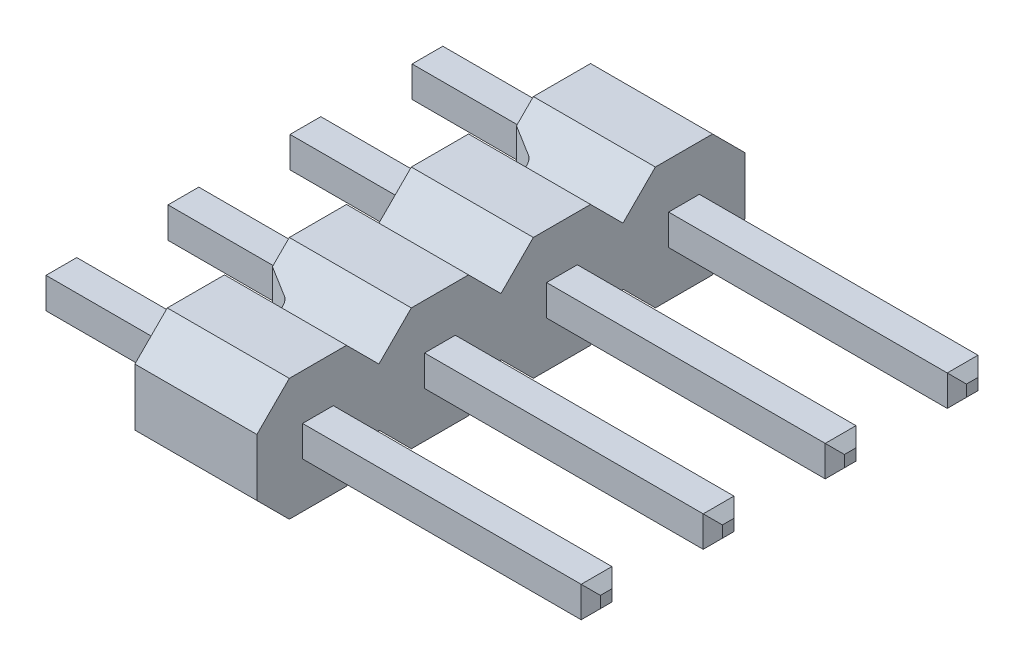
SolidWorks part; units mm, degrees
ref_plane "Alzado" through (0, 0, 0) normal (0, 0, 1) x (1, 0, 0)
ref_plane "Planta" through (0, 0, 0) normal (0, 1, 0) x (1, 0, 0)
ref_plane "Vista lateral" through (0, 0, 0) normal (1, 0, 0) x (0, 0, -1)
sketch "Croquis1" plane through (0, 0, 0) normal (1, 0, 0) x (0, 0, -1)
  line L0 (-0.5955, 1.27) -> (-1.27, 0.5955)
  line L1 (0.5955, 1.27) -> (-0.5955, 1.27)
  line L2 (1.27, 0.5955) -> (1.27, -0.5955)
  line L3 (0.5955, -1.27) -> (-0.5955, -1.27)
  line L4 (-1.27, 0.5955) -> (-1.27, -0.5955)
  line L5 (1.27, 1.27) -> (-1.27, -1.27) construction
  line L6 (1.27, -1.27) -> (-1.27, 1.27) construction
  line L7 (-0.5955, -1.27) -> (-1.27, -0.5955)
  line L8 (1.27, -0.5955) -> (0.5955, -1.27)
  line L9 (1.27, 0.5955) -> (0.5955, 1.27)
  line L10 (0, 0) -> (2.54, 0) construction
  line L11 (2.54, 0) -> (2.54, 3.1915) construction
  line L12 (0, 0) -> (0, 2.4434) construction
  line L13 (1.27, 0.5955) -> (1.27, 2.4434) construction
  line L14 (1.27, -0.5955) -> (1.9445, -1.27)
  line L15 (1.27, 0.5955) -> (1.9445, 1.27)
  line L16 (3.1355, -1.27) -> (3.81, -0.5955)
  line L17 (3.81, 0.5955) -> (3.81, -0.5955)
  line L18 (1.9445, -1.27) -> (3.1355, -1.27)
  line L19 (1.9445, 1.27) -> (3.1355, 1.27)
  line L20 (3.1355, 1.27) -> (3.81, 0.5955)
  line L21 (2.22, -0.32) -> (2.86, 0.32) construction
  line L22 (0.32, 0.32) -> (-0.32, 0.32)
  line L23 (0.32, 0.32) -> (0.32, -0.32)
  line L24 (0.32, -0.32) -> (-0.32, -0.32)
  line L25 (-0.32, 0.32) -> (-0.32, -0.32)
  line L26 (0.32, 0.32) -> (-0.32, -0.32) construction
  line L27 (0.32, -0.32) -> (-0.32, 0.32) construction
  line L28 (2.22, 0.32) -> (2.86, -0.32) construction
  line L29 (2.86, 0.32) -> (2.86, -0.32)
  line L30 (2.22, -0.32) -> (2.86, -0.32)
  line L31 (2.22, 0.32) -> (2.22, -0.32)
  line L32 (2.22, 0.32) -> (2.86, 0.32)
  point P0 (0, 0)
  dimension "D1" = 2.54
  dimension "D2" = 2.54
  dimension "D3" = 2.54
  dimension "D4" = 0.64
  dimension "D5" = 0.64
extrude "Saliente-Extruir1" add sketch "Croquis1" along normal blind 2.54 contours L2 L9 L1 L0 L4 L7 L3 L8 L25 L22 L23 L24 | L20 L19 L15 L2 L14 L18 L16 L17 L31 L32 L29 L30
sketch "Croquis2" plane through (0, 0, 0) normal (0, 1, 0) x (1, 0, 0)
  line L0 (0, 1.27) -> (0.5165, 1.27) construction
  line L1 (2.54, 1.27) -> (0, 1.27) construction
  line L2 (0.5165, 1.2433) -> (0.5165, 1.2967)
  line L3 (0.4575, 1.3879) -> (0, 1.5936)
  line L4 (0, 1.27) -> (0, 1.9445) construction
  line L5 (0.4575, 1.1521) -> (0, 0.9464)
  line L6 (0, 1.5936) -> (0, 0.9464)
  arc A0 (0.5165, 1.2967) -> (0.4575, 1.3879) centre (0.4165, 1.2967) ccw
  arc A1 (0.5165, 1.2433) -> (0.4575, 1.1521) centre (0.4165, 1.2433) cw
  dimension "D1" = 0.1
extrude "Cortar-Extruir1" cut sketch "Croquis2" against normal blind 2.54 and the other way blind 2.54
sketch "Croquis3" plane through (0, 0, 0) normal (1, 0, 0) x (0, 0, -1)
  line L1 (-0.32, -0.32) -> (0.32, -0.32)
  line L2 (-0.32, -0.32) -> (-0.32, 0.32)
  line L3 (-0.32, 0.32) -> (0.32, 0.32)
  line L4 (0.32, -0.32) -> (0.32, 0.32)
  line L5 (2.22, -0.32) -> (2.86, -0.32)
  line L6 (2.22, -0.32) -> (2.22, 0.32)
  line L7 (2.22, 0.32) -> (2.86, 0.32)
  line L8 (2.86, -0.32) -> (2.86, 0.32)
extrude "Saliente-Extruir2" add sketch "Croquis3" along normal blind 8.54 and the other way blind 3 separate body
chamfer "Chaflán1" distance 0.2 angle 45 8 edges at (-3, -0.32, 0) (-3, 0, -0.32) (-3, 0.32, 0) (-3, 0, 0.32) (8.54, 0.32, 0) (8.54, 0, -0.32) (8.54, -0.32, 0) (8.54, 0, 0.32)
chamfer "Chaflán2" distance 0.2 angle 45 8 edges at (8.54, 0.32, -2.54) (8.54, 0, -2.86) (8.54, -0.32, -2.54) (8.54, 0, -2.22) (-3, -0.32, -2.54) (-3, 0, -2.86) (-3, 0.32, -2.54) (-3, 0, -2.22)
mirror "Mirror3" about plane through (2.54, 0, 1.27) normal (0, 0, -1) of bodies 104 103
mirror "Mirror5" about plane through (2.54, 0, 1.27) normal (0, 0, -1) of bodies 102
